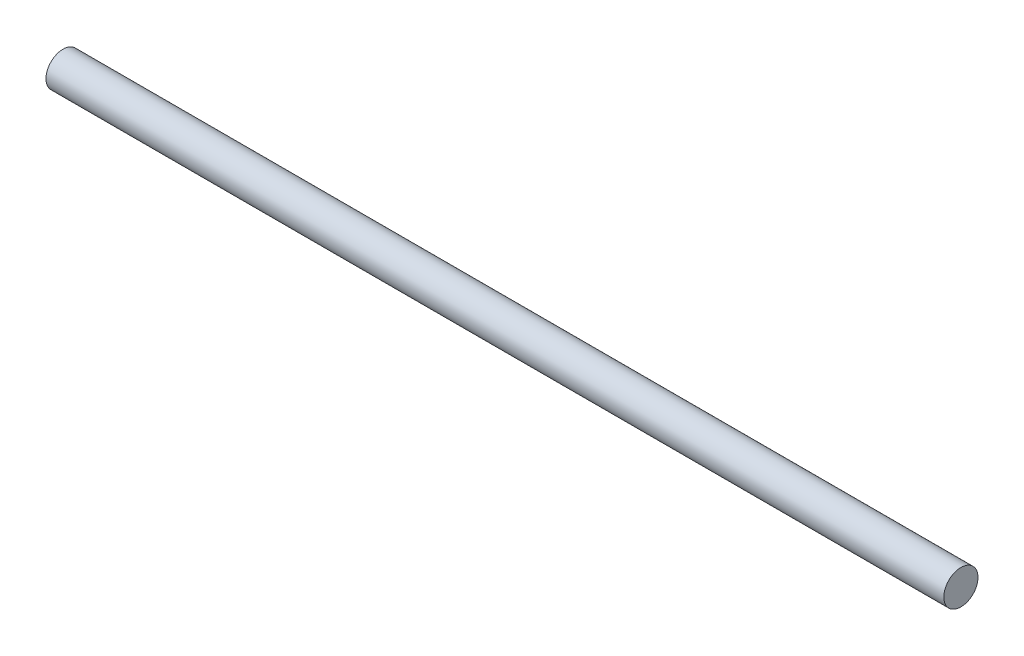
SolidWorks part; units mm, degrees
ref_plane "前视基准面" through (0, 0, 0) normal (0, 0, 1) x (1, 0, 0)
ref_plane "上视基准面" through (0, 0, 0) normal (0, 1, 0) x (1, 0, 0)
ref_plane "右视基准面" through (0, 0, 0) normal (1, 0, 0) x (0, 0, -1)
sketch "草图1" plane through (0, 0, 0) normal (1, 0, 0) x (0, 0, -1)
  circle A0 centre (-8.755, 16.6527) radius 4
extrude "凸台-拉伸1" add sketch "草图1" along normal blind 210
